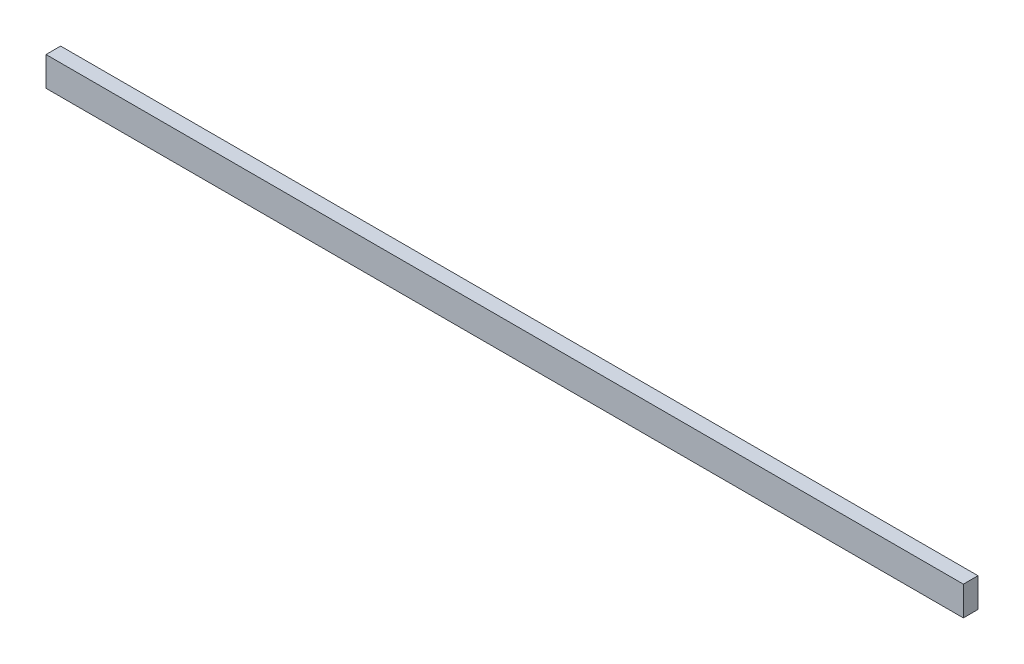
SolidWorks part; units mm, degrees
material "Pine"
ref_plane "Piano frontale" through (0, 0, 0) normal (0, 0, 1) x (1, 0, 0)
ref_plane "Piano superiore" through (0, 0, 0) normal (0, 1, 0) x (1, 0, 0)
ref_plane "Piano destro" through (0, 0, 0) normal (1, 0, 0) x (0, 0, -1)
sketch "Sketch1" plane through (0, 0, 0) normal (0, 0, 1) x (1, 0, 0)
  line L1 (0, 0) -> (94, 0)
  line L2 (0, 0) -> (0, 3)
  line L3 (0, 3) -> (94, 3)
  line L4 (94, 0) -> (94, 3)
  dimension "D1" = 94
  dimension "D2" = 3
extrude "Boss-Extrude1" add sketch "Sketch1" along normal blind 1.5
scale "Scale1" scale about origin uniform scaling yes scale factor 10
